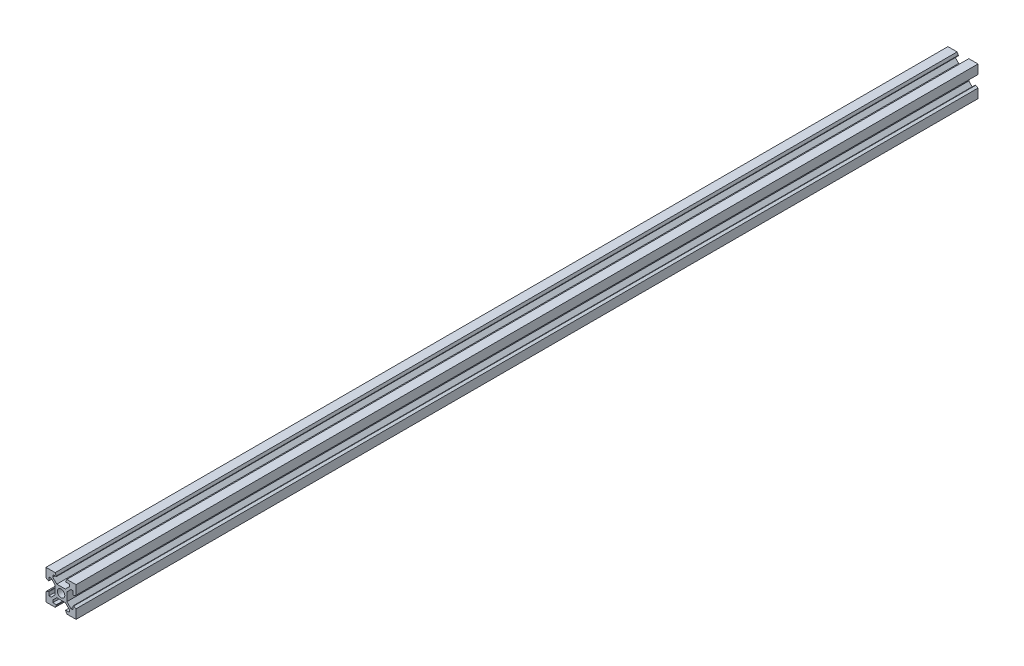
SolidWorks part; units mm, degrees
ref_plane "Front Plane" through (0, 0, 0) normal (0, 0, 1) x (1, 0, 0)
ref_plane "Top Plane" through (0, 0, 0) normal (0, 1, 0) x (1, 0, 0)
ref_plane "Right Plane" through (0, 0, 0) normal (1, 0, 0) x (0, 0, -1)
sketch "Sketch1" plane through (0, 0, 0) normal (0, 0, 1) x (1, 0, 0)
  line L0 (0, 20) -> (0, 13.8958)
  line L1 (0, 0) -> (20, 0)
  line L2 (0, 0) -> (0, 20)
  line L3 (0, 20) -> (20, 20)
  line L4 (20, 0) -> (20, 20)
  line L5 (0, 13.8958) -> (1.56, 13.1)
  line L6 (1.56, 13.1) -> (1.9, 13.1)
  line L7 (1.9, 13.1) -> (1.9, 15.5)
  line L8 (1.9, 15.5) -> (3.4393, 15.5)
  line L9 (3.4393, 15.5) -> (6.2656, 12.6737)
  line L10 (6.2656, 12.6737) -> (7.3263, 13.7344)
  line L11 (7.3263, 13.7344) -> (4.5, 16.5607)
  line L12 (4.5, 16.5607) -> (4.5, 18.1)
  line L13 (4.5, 18.1) -> (6.9, 18.1)
  line L14 (6.9, 18.1) -> (6.9, 18.44)
  line L15 (6.9, 18.44) -> (6.1, 20)
  line L16 (6.1, 20) -> (0, 20)
  line L17 (10, 10) -> (6.1, 13.9)
  line L18 (6.1, 6.1) -> (13.9, 6.1)
  line L19 (6.1, 6.1) -> (6.1, 13.9)
  line L20 (6.1, 13.9) -> (13.9, 13.9)
  line L21 (13.9, 6.1) -> (13.9, 13.9)
  line L22 (6.796, 13.204) -> (4.0494, 15.9506)
  line L23 (10, 10) -> (10, 24.9145) construction
  line L24 (13.1, 18.44) -> (13.9, 20)
  line L25 (13.1, 18.1) -> (13.1, 18.44)
  line L26 (15.5, 18.1) -> (13.1, 18.1)
  line L27 (15.5, 16.5607) -> (15.5, 18.1)
  line L28 (12.6737, 13.7344) -> (15.5, 16.5607)
  line L29 (13.7344, 12.6737) -> (12.6737, 13.7344)
  line L30 (16.5607, 15.5) -> (13.7344, 12.6737)
  line L31 (18.1, 15.5) -> (16.5607, 15.5)
  line L32 (18.1, 13.1) -> (18.1, 15.5)
  line L33 (18.44, 13.1) -> (18.1, 13.1)
  line L34 (20, 13.8958) -> (18.44, 13.1)
  line L35 (10, 10) -> (22.1718, 10)
  line L36 (20, 6.1042) -> (18.44, 6.9)
  line L37 (18.44, 6.9) -> (18.1, 6.9)
  line L38 (18.1, 6.9) -> (18.1, 4.5)
  line L39 (18.1, 4.5) -> (16.5607, 4.5)
  line L40 (16.5607, 4.5) -> (13.7344, 7.3263)
  line L41 (13.7344, 7.3263) -> (12.6737, 6.2656)
  line L42 (12.6737, 6.2656) -> (15.5, 3.4393)
  line L43 (15.5, 3.4393) -> (15.5, 1.9)
  line L44 (15.5, 1.9) -> (13.1, 1.9)
  line L45 (13.1, 1.9) -> (13.1, 1.56)
  line L46 (13.1, 1.56) -> (13.9, 0)
  line L47 (6.9, 1.56) -> (6.1, 0)
  line L48 (6.9, 1.9) -> (6.9, 1.56)
  line L49 (4.5, 1.9) -> (6.9, 1.9)
  line L50 (4.5, 3.4393) -> (4.5, 1.9)
  line L51 (7.3263, 6.2656) -> (4.5, 3.4393)
  line L52 (6.2656, 7.3263) -> (7.3263, 6.2656)
  line L53 (3.4393, 4.5) -> (6.2656, 7.3263)
  line L54 (1.9, 4.5) -> (3.4393, 4.5)
  line L55 (1.9, 6.9) -> (1.9, 4.5)
  line L56 (1.56, 6.9) -> (1.9, 6.9)
  line L57 (0, 6.1042) -> (1.56, 6.9)
  circle A0 centre (10, 10) radius 2.5
  point P21 (2.6697, 15.5)
  dimension "D3" = 5
  dimension "D1" = 20
  dimension "D2" = 20
  dimension "D4" = 10
  dimension "D5" = 10
  dimension "D6" = 7.8
  dimension "D7" = 7.8
  dimension "D8" = 6.1
  dimension "D9" = 6.1
  dimension "D10" = 6.9
  dimension "D11" = 6.9
  dimension "D12" = 6.1042
  dimension "D13" = 6.1
  dimension "D14" = 0.34
  dimension "D15" = 0.34
  dimension "D16" = 1.9
  dimension "D17" = 4.5
  dimension "D18" = 4.5
  dimension "D19" = 1.5
  dimension "D20" = 1.9
extrude "Boss-Extrude1" add sketch "Sketch1" along normal blind 600
